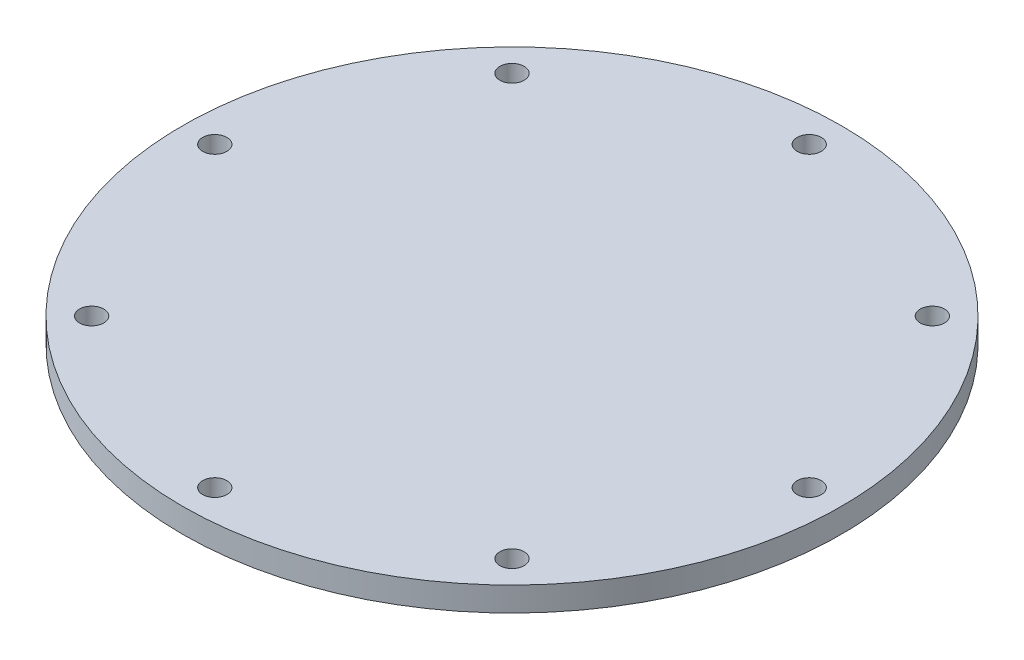
SolidWorks part; units mm, degrees
ref_plane "前视基准面" through (0, 0, 0) normal (0, 0, 1) x (1, 0, 0)
ref_plane "上视基准面" through (0, 0, 0) normal (0, 1, 0) x (1, 0, 0)
ref_plane "右视基准面" through (0, 0, 0) normal (1, 0, 0) x (0, 0, -1)
sketch "草图1" plane through (0, 0, 0) normal (0, 1, 0) x (1, 0, 0)
  line L0 (-26, 26) -> (0, 0) construction
  line L5 (-26, 26) -> (-28.8284, 28.8284) construction
  line L7 (-26, -26) -> (26, -26) construction
  line L8 (-26, -26) -> (-26, 26) construction
  line L9 (-26, 26) -> (26, 26) construction
  line L10 (26, -26) -> (26, 26) construction
  circle A0 centre (-26, 26) radius 1.5
  circle A1 centre (26, 26) radius 1.5
  circle A2 centre (26, -26) radius 1.5
  circle A3 centre (-26, -26) radius 1.5
  circle A8 centre (0, 0) radius 40.7696
  circle A9 centre (0, 36.7696) radius 1.5
  circle A10 centre (36.7696, 0) radius 1.5
  circle A11 centre (0, -36.7696) radius 1.5
  circle A12 centre (-36.7696, 0) radius 1.5
  point P0 (0, 0)
  point P5 (0, 0)
  point P21 (0, 0)
  dimension "D3" = 3
  dimension "D5" = 2
  dimension "D1" = 4
  dimension "D2" = 52
  dimension "D4" = 4
extrude "凸台-拉伸1" add sketch "草图1" along normal blind 3
